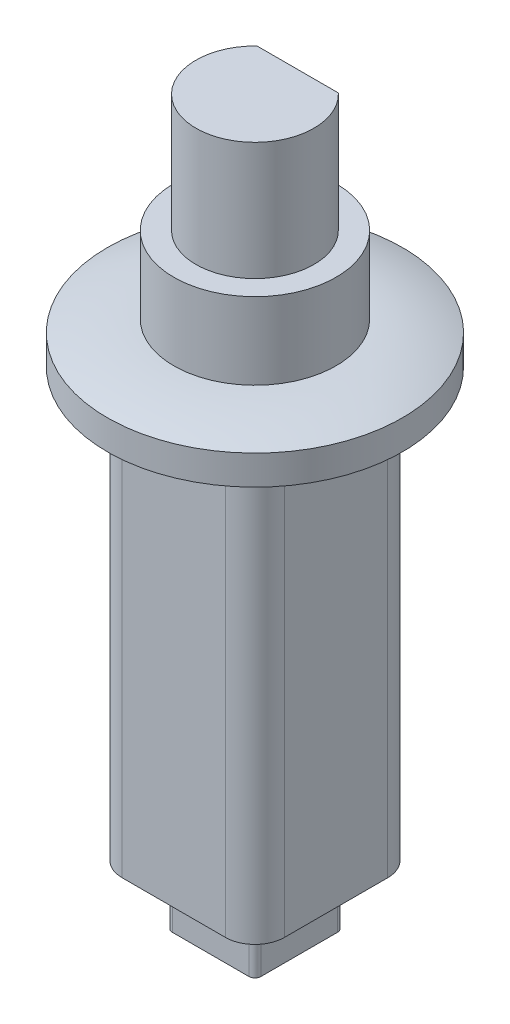
SolidWorks part; units mm, degrees
ref_plane "Front Plane" through (0, 0, 0) normal (0, 0, 1) x (1, 0, 0)
ref_plane "Top Plane" through (0, 0, 0) normal (0, 1, 0) x (1, 0, 0)
ref_plane "Right Plane" through (0, 0, 0) normal (1, 0, 0) x (0, 0, -1)
sketch "Sketch1" plane through (0, 0, 0) normal (0, 0, 1) x (1, 0, 0)
  line L0 (0, 8) -> (2, 8)
  line L1 (2, 8) -> (2, 4)
  line L2 (2, 4) -> (2.75, 4)
  line L3 (2.75, 4) -> (2.75, 1.4)
  line L4 (5, 1) -> (5, 0)
  line L5 (5, 0) -> (0, 0)
  line L6 (0, 0) -> (0, 8)
  line L7 (0, 8) -> (0, 0) construction
  arc A0 (2.75, 1.4) -> (5, 1) centre (2.75, -5.1281) cw
  dimension "D1" = 4
  dimension "D2" = 4
  dimension "D3" = 1.4
  dimension "5.5" = 5.5
  dimension "D4" = 10
  dimension "D5" = 1
  dimension "D6" = 4
revolve "Revolve1" add sketch "Sketch1" angle 360 about L7
sketch "Sketch2" plane through (0, 8, 0) normal (0, 1, 0) x (1, 0, 0)
  line L0 (-1.3775, 1.45) -> (1.3775, 1.45)
  circle A0 centre (0, 0) radius 2 construction
  circle A1 centre (0, 0) radius 2 construction
  circle A3 centre (0, 0) radius 2
  arc A4 (1.3775, 1.45) -> (-1.3775, 1.45) centre (0, 0) ccw
  dimension "D1" = 1.45
  dimension "D2" = 0
extrude "Cut-Extrude1" cut sketch "Sketch2" against normal up to surface (4 mm away) up to face at (-2, 4, 0)
sketch "Sketch3" plane through (0, 0, 0) normal (0, -1, 0) x (1, 0, 0)
  line L1 (-1.75, -2.75) -> (1.75, -2.75)
  line L2 (-2.75, -1.75) -> (-2.75, 1.75)
  line L3 (-1.75, 2.75) -> (1.75, 2.75)
  line L4 (2.75, -1.75) -> (2.75, 1.75)
  line L5 (-2.75, -2.75) -> (2.75, 2.75) construction
  line L6 (-2.75, 2.75) -> (2.75, -2.75) construction
  arc A0 (1.75, 2.75) -> (2.75, 1.75) centre (1.75, 1.75) cw
  arc A1 (1.75, -2.75) -> (2.75, -1.75) centre (1.75, -1.75) ccw
  arc A2 (-1.75, -2.75) -> (-2.75, -1.75) centre (-1.75, -1.75) cw
  arc A3 (-2.75, 1.75) -> (-1.75, 2.75) centre (-1.75, 1.75) cw
  point P0 (0, 0)
  dimension "D3" = 1
  dimension "D1" = 5.5
  dimension "D2" = 5.5
extrude "Boss-Extrude1" add sketch "Sketch3" along normal blind 14.5
sketch "Sketch5" plane through (0, -14.5, 0) normal (0, -1, 0) x (1, 0, 0)
  line L1 (1.3, -1.5) -> (-1.3, -1.5)
  line L2 (1.5, -1.3) -> (1.5, 1.3)
  line L3 (1.3, 1.5) -> (-1.3, 1.5)
  line L4 (-1.5, -1.3) -> (-1.5, 1.3)
  line L5 (1.5, -1.5) -> (-1.5, 1.5) construction
  line L6 (1.5, 1.5) -> (-1.5, -1.5) construction
  arc A0 (1.5, 1.3) -> (1.3, 1.5) centre (1.3, 1.3) ccw
  arc A1 (1.3, -1.5) -> (1.5, -1.3) centre (1.3, -1.3) ccw
  arc A2 (-1.3, -1.5) -> (-1.5, -1.3) centre (-1.3, -1.3) cw
  arc A3 (-1.3, 1.5) -> (-1.5, 1.3) centre (-1.3, 1.3) ccw
  point P0 (0, 0)
  dimension "D3" = 0.2
  dimension "D1" = 3
  dimension "D2" = 3
extrude "Boss-Extrude2" add sketch "Sketch5" along normal blind 2
